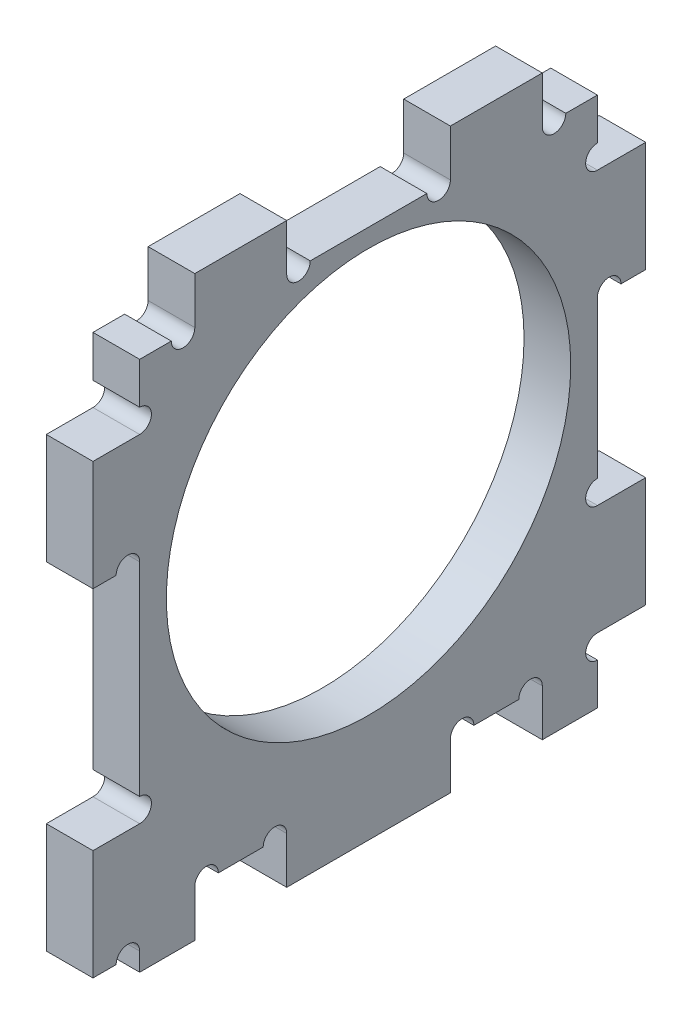
SolidWorks part; units mm, degrees
ref_plane "Front Plane" through (0, 0, 0) normal (0, 0, 1) x (1, 0, 0)
ref_plane "Top Plane" through (0, 0, 0) normal (0, 1, 0) x (1, 0, 0)
ref_plane "Right Plane" through (0, 0, 0) normal (1, 0, 0) x (0, 0, -1)
sketch "Sketch1" plane through (0, 0, 0) normal (1, 0, 0) x (0, 0, -1)
  line L0 (-62.2626, 60) -> (-62.2626, 42.3)
  line L1 (-62.2626, 42.3) -> (-74.9626, 42.3)
  line L2 (-74.9626, 42.3) -> (-74.9626, 12.3)
  line L3 (-74.9626, 12.3) -> (-62.2626, 12.3)
  line L4 (-62.2626, 12.3) -> (-62.2626, -49.4)
  line L5 (-62.2626, -49.4) -> (-74.9626, -49.4)
  line L6 (-74.9626, -49.4) -> (-74.9626, -79.4)
  line L7 (-74.9626, -79.4) -> (-62.2626, -79.4)
  line L8 (-62.2626, -79.4) -> (-62.2626, -84.4)
  line L9 (-47.2626, -84.4) -> (-47.2626, -71.7)
  line L10 (62.2626, -84.4) -> (62.2626, -66.7)
  line L11 (62.2626, -66.7) -> (75.3938, -66.7)
  line L12 (75.3938, -66.7) -> (75.3938, -36.7)
  line L13 (75.3938, -36.7) -> (62.2626, -36.7)
  line L14 (62.2626, -36.7) -> (62.2626, 12.3)
  line L15 (62.2626, 12.3) -> (75.3938, 12.3)
  line L16 (75.3938, 12.3) -> (75.3938, 42.3)
  line L17 (75.3938, 42.3) -> (62.2626, 42.3)
  line L18 (62.2626, 42.3) -> (62.2626, 60)
  line L19 (62.2626, 60) -> (-62.2626, 60) construction
  line L20 (0, 60) -> (0, 0) construction
  line L21 (-62.2626, 60) -> (-47.2626, 60)
  line L22 (-47.2626, 60) -> (-47.2626, 72.7)
  line L23 (-47.2626, 72.7) -> (-22.2626, 72.7)
  line L24 (-22.2626, 72.7) -> (-22.2626, 60)
  line L25 (-22.2626, 60) -> (0, 60)
  line L26 (0, 60) -> (22.2626, 60)
  line L27 (22.2626, 60) -> (22.2626, 72.7)
  line L28 (22.2626, 72.7) -> (47.2626, 72.7)
  line L29 (47.2626, 72.7) -> (47.2626, 60)
  line L30 (47.2626, 60) -> (62.2626, 60)
  line L31 (-62.2626, -84.4) -> (-47.2626, -84.4)
  line L32 (-47.2626, -71.7) -> (-22.2626, -71.7)
  line L33 (-22.2626, -71.7) -> (-22.2626, -84.4)
  line L34 (-22.2626, -84.4) -> (22.2626, -84.4)
  line L35 (22.2626, -71.7) -> (22.2626, -84.4)
  line L36 (47.2626, -71.7) -> (22.2626, -71.7)
  line L37 (47.2626, -84.4) -> (47.2626, -71.7)
  line L38 (47.2626, -84.4) -> (62.2626, -84.4)
  circle A0 centre (0, 0) radius 60 construction
  circle A1 centre (0, 0) radius 55
  dimension "D8" = 120
  dimension "D9" = 110
  dimension "D1" = 124.5252
  dimension "D2" = 139.4
  dimension "D3" = 12.7
  dimension "D4" = 13.1312
  dimension "D5" = 30
  dimension "D6" = 17.7
  dimension "D7" = 49
  dimension "D10" = 12.7
  dimension "D11" = 25
  dimension "D12" = 15
  dimension "D13" = 5
extrude "Boss-Extrude1" add sketch "Sketch1" along normal blind 12.7
sketch "Sketch2" plane through (12.7, 0, 0) normal (1, 0, 0) x (0, 0, -1)
  line L0 (-62.2626, 60) -> (-62.2626, 42.3) construction
  line L1 (-74.9626, 12.3) -> (-62.2626, 12.3) construction
  line L2 (-62.2626, 12.3) -> (-62.2626, -49.4) construction
  line L4 (62.2626, -84.4) -> (62.2626, -66.7) construction
  line L5 (62.2626, -36.7) -> (62.2626, 12.3) construction
  line L6 (62.2626, 12.3) -> (75.3938, 12.3) construction
  line L7 (62.2626, 42.3) -> (62.2626, 60) construction
  line L8 (-47.2626, 60) -> (-62.2626, 60) construction
  line L9 (22.2626, 60) -> (-22.2626, 60) construction
  line L10 (62.2626, 60) -> (47.2626, 60) construction
  line L11 (-74.9626, -79.4) -> (-62.2626, -79.4) construction
  line L12 (-47.2626, -71.7) -> (-22.2626, -71.7) construction
  line L13 (22.2626, -71.7) -> (47.2626, -71.7) construction
  circle A0 centre (-62.2626, 45.5) radius 3.2
  circle A1 centre (-65.4626, 12.3) radius 3.2
  circle A2 centre (-62.2626, -46.2) radius 3.2
  circle A3 centre (-65.4626, -79.4) radius 3.2
  circle A4 centre (62.2626, -69.9) radius 3.2
  circle A5 centre (62.2626, -33.5) radius 3.2
  circle A6 centre (65.4626, 12.3) radius 3.2
  circle A7 centre (62.2626, 45.5) radius 3.2
  circle A8 centre (-50.4626, 60) radius 3.2
  circle A9 centre (-19.0626, 60) radius 3.2
  circle A10 centre (19.0626, 60) radius 3.2
  circle A11 centre (50.4626, 60) radius 3.2
  circle A12 centre (-44.0626, -71.7) radius 3.2
  circle A13 centre (-25.4626, -71.7) radius 3.2
  circle A14 centre (25.4626, -71.7) radius 3.2
  circle A15 centre (44.0626, -71.7) radius 3.2
  dimension "D1" = 6.4
extrude "Cut-Extrude1" cut sketch "Sketch2" against normal through all
